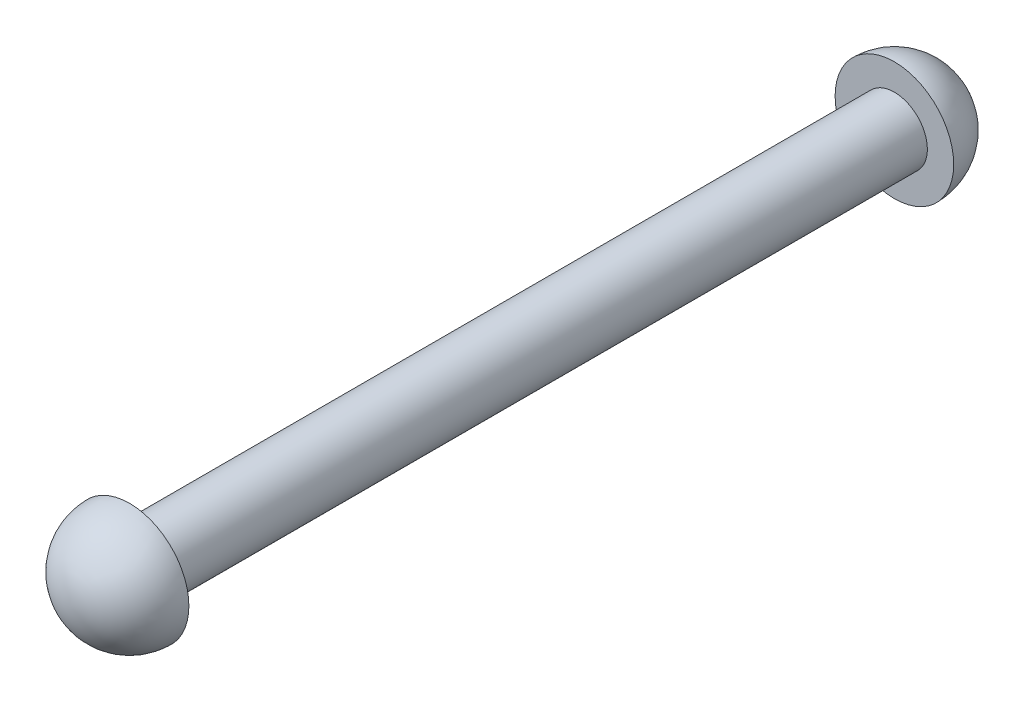
SolidWorks part; units mm, degrees
material "AISI 1020"
ref_plane "Front Plane" through (0, 0, 0) normal (0, 0, 1) x (1, 0, 0)
ref_plane "Top Plane" through (0, 0, 0) normal (0, 1, 0) x (1, 0, 0)
ref_plane "Right Plane" through (0, 0, 0) normal (1, 0, 0) x (0, 0, -1)
sketch "Sketch2" plane through (0, 0, 0) normal (1, 0, 0) x (0, 0, -1)
  line L0 (-34.29, -5.316) -> (-34.29, -2.956)
  line L1 (-34.29, -2.956) -> (34.29, -2.956)
  line L2 (-34.29, -2.956) -> (-34.29, 2.956)
  line L3 (-34.29, 2.956) -> (34.29, 2.956)
  line L4 (34.29, -2.956) -> (34.29, 2.956)
  line L5 (-39.606, 0) -> (39.606, 0) construction
  line L7 (-34.29, 2.956) -> (-34.29, 5.316)
  line L8 (34.29, 2.956) -> (34.29, 5.316)
  line L9 (34.29, -5.316) -> (34.29, -2.956)
  arc A0 (-34.29, 5.316) -> (-34.29, -5.316) centre (-34.29, 0) ccw
  arc A1 (34.29, -5.316) -> (34.29, 5.316) centre (34.29, 0) ccw
  point P0 (0, 0)
  dimension "D1" = 68.58
revolve "Revolve1" add sketch "Sketch2" angle 360 about L5
